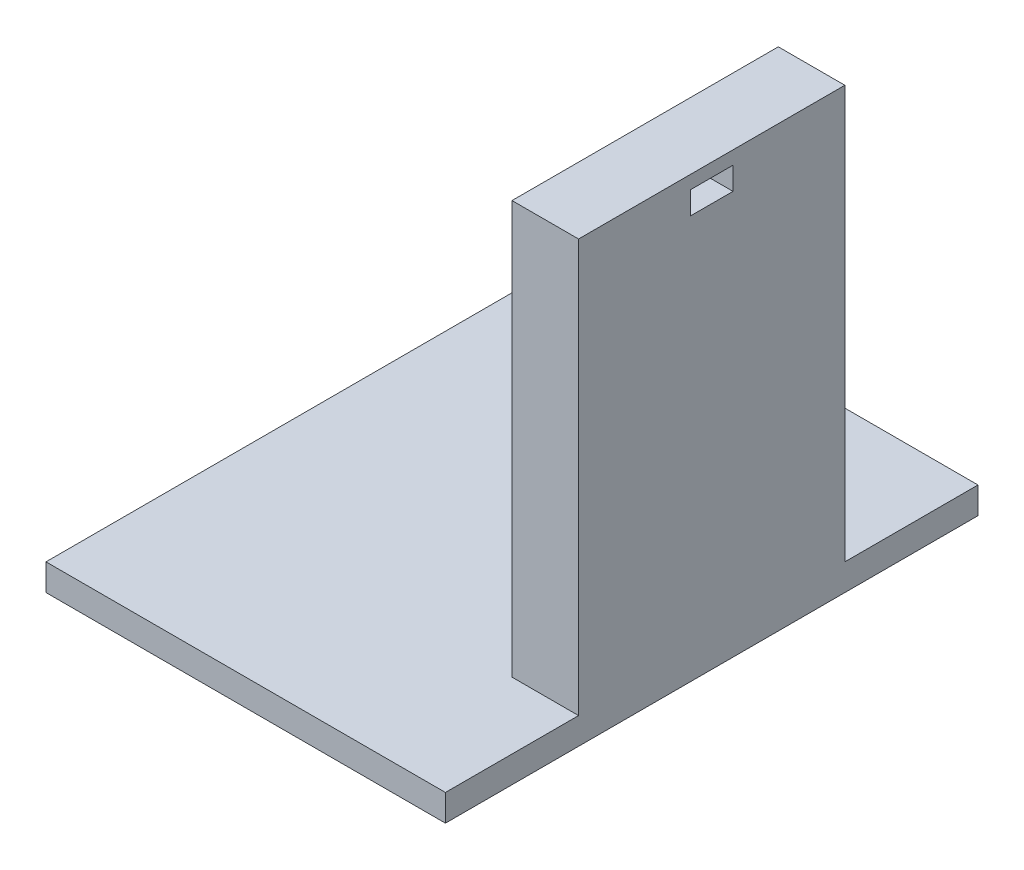
SolidWorks part; units mm, degrees
ref_plane "Plan de face" through (0, 0, 0) normal (0, 0, 1) x (1, 0, 0)
ref_plane "Plan de dessus" through (0, 0, 0) normal (0, 1, 0) x (1, 0, 0)
ref_plane "Plan de droite" through (0, 0, 0) normal (1, 0, 0) x (0, 0, -1)
sketch "Esquisse2" plane through (0, 0, 0) normal (0, 1, 0) x (1, 0, 0)
  line L0 (54.6919, 181.7) -> (54.6919, -18.3)
  line L1 (-95.3081, 181.7) -> (54.6919, 181.7)
  line L2 (-95.3081, 181.7) -> (-95.3081, -18.3)
  line L3 (-95.3081, -18.3) -> (54.6919, -18.3)
extrude "Boss.-Extru.6" add sketch "Esquisse2" along normal blind 10
sketch "Esquisse4" plane through (0, 0, 0) normal (0, 1, 0) x (1, 0, 0)
  line L0 (29.6919, 31.7) -> (54.6919, 31.7)
  line L1 (29.6919, 31.7) -> (29.6919, 131.7)
  line L2 (29.6919, 131.7) -> (54.6919, 131.7)
  line L3 (54.6919, 31.7) -> (54.6919, 131.7)
  line L4 (54.6919, -18.3) -> (54.6919, 181.7) construction
  line L5 (54.6919, -18.3) -> (54.6919, 181.7)
extrude "Boss.-Extru.7" add sketch "Esquisse4" along normal blind 160 contours L0 L3 L2 L1
sketch "Esquisse8" plane through (29.6919, 0, 0) normal (-1, 0, 0) x (0, 0, 1)
  line L0 (-93.9, 139.9717) -> (-69.5, 139.9717)
  line L1 (-93.9, 139.9717) -> (-93.9, 160)
  line L2 (-93.9, 160) -> (-69.5, 160)
  line L3 (-69.5, 139.9717) -> (-69.5, 160)
  line L4 (-31.7, 160) -> (-131.7, 160) construction
  point P6 (-81.7, 160)
  dimension "D1" = 20.0283
  dimension "D2" = 24.4
extrude "Enlèv. mat.-Extru.1" cut sketch "Esquisse8" against normal blind 12.2
sketch "Esquisse9" plane through (41.8919, 0, 0) normal (-1, 0, 0) x (0, 0, 1)
  line L0 (-87.7, 158.4859) -> (-87.7, 153.4859) construction
  line L1 (-87.7, 153.4859) -> (-75.7, 153.4859) construction
  line L2 (-75.7, 153.4859) -> (-75.7, 158.4859) construction
  line L3 (-75.7, 158.4859) -> (-87.7, 158.4859) construction
  line L4 (-81.7, 160) -> (-81.7, 158.4859) construction
  line L6 (-69.5, 160) -> (-93.9, 160) construction
  line L7 (-87.7, 158.4859) -> (-87.7, 153.4859)
  line L8 (-87.7, 153.4859) -> (-75.7, 153.4859)
  line L9 (-75.7, 153.4859) -> (-75.7, 158.4859)
  line L10 (-75.7, 158.4859) -> (-87.7, 158.4859)
  point P6 (-81.7, 158.4859)
  dimension "D1" = 1.5141
  dimension "D2" = 5
  dimension "D3" = 12
extrude "Enlèv. mat.-Extru.2" cut sketch "Esquisse9" against normal blind 42.2
sketch "Esquisse11" plane through (41.8919, 0, 0) normal (-1, 0, 0) x (0, 0, 1)
  line L0 (-69.5, 160) -> (-93.9, 160) construction
  line L1 (-89.7, 160) -> (-73.7, 160)
  line L2 (-89.7, 160) -> (-89.7, 151.4859)
  line L3 (-89.7, 151.4859) -> (-73.7, 151.4859)
  line L4 (-73.7, 160) -> (-73.7, 151.4859)
  line L5 (-87.7, 155.7429) -> (-89.7, 155.7429) construction
  line L6 (-87.7, 158.4859) -> (-87.7, 153.4859) construction
  line L7 (-75.7, 155.9859) -> (-73.7, 155.9859) construction
  line L8 (-75.7, 153.4859) -> (-75.7, 158.4859) construction
  line L9 (-81.7, 153.4859) -> (-81.7, 151.4859) construction
  line L10 (-87.7, 153.4859) -> (-75.7, 153.4859) construction
  dimension "D1" = 2
  dimension "D2" = 2
  dimension "D3" = 2
extrude "Enlèv. mat.-Extru.3" cut sketch "Esquisse11" against normal blind 42.2
sketch "Esquisse12" plane through (29.6919, 0, 0) normal (-1, 0, 0) x (0, 0, 1)
  line L0 (-94.4, 160) -> (-94.4, 139.97)
  line L1 (-93.9, 160) -> (-131.7, 160) construction
  line L3 (-69, 139.97) -> (-69, 160)
  line L4 (-31.7, 160) -> (-69.5, 160) construction
  line L5 (-69, 160) -> (-69.5, 160)
  line L6 (-69.5, 160) -> (-69.5, 139.9717)
  line L8 (-93.9, 139.9717) -> (-93.9, 160)
  line L9 (-93.9, 160) -> (-94.4, 160)
  line L10 (-79.5159, 139.9717) -> (-79.5159, 139.4717) construction
  line L11 (-69, 139.97) -> (-69.5, 139.9717)
  line L13 (-93.9, 139.9717) -> (-94.4, 139.97)
  dimension "D1" = 0.5
  dimension "D2" = 0.5
  dimension "D3" = 20.0283
  dimension "D4" = 20.03
  dimension "D5" = 20.03
extrude "Enlèv. mat.-Extru.6" cut sketch "Esquisse12" against normal blind 12.2
sketch "Esquisse13" plane through (0, 160, 0) normal (0, 1, 0) x (1, 0, 0)
  line L1 (29.6919, 131.7) -> (54.6919, 131.7)
  line L2 (29.6919, 131.7) -> (29.6919, 31.7)
  line L3 (29.6919, 31.7) -> (54.6919, 31.7)
  line L4 (54.6919, 131.7) -> (54.6919, 31.7)
extrude "Boss.-Extru.8" add sketch "Esquisse13" along normal blind 5
sketch "Esquisse14" plane through (29.6919, 0, 0) normal (-1, 0, 0) x (0, 0, 1)
  line L0 (-94.4, 160) -> (-94.4, 160.5)
  line L2 (-94.4, 160) -> (-69, 160)
  line L4 (-69, 160) -> (-69, 160.5)
  line L5 (-69, 160.5) -> (-94.4, 160.5)
  dimension "D1" = 0.5
extrude "Enlèv. mat.-Extru.7" cut sketch "Esquisse14" against normal blind 12.2
sketch "Esquisse19" plane through (41.8919, 0, 0) normal (-1, 0, 0) x (0, 0, 1)
  line L1 (-106.7, 5) -> (-56.7, 5)
  line L2 (-106.7, 5) -> (-106.7, 0)
  line L3 (-106.7, 0) -> (-56.7, 0)
  line L4 (-56.7, 5) -> (-56.7, 0)
  line L5 (-181.7, 0) -> (18.3, 0) construction
  point P8 (-81.7, 0)
  point P9 (-81.7, 0)
  dimension "D1" = 50
  dimension "D2" = 5
extrude "Enlèv. mat.-Extru.8" cut sketch "Esquisse19" along normal blind 150
sketch "Esquisse21" plane through (0, 0, 0) normal (1, 0, 0) x (0, 0, -1)
  line L0 (56.7, 5) -> (106.7, 5)
  line L1 (56.7, 5) -> (56.7, 0)
  line L2 (56.7, 0) -> (106.7, 0)
  line L3 (106.7, 5) -> (106.7, 0)
  line L4 (181.7, 0) -> (-18.3, 0) construction
  point P4 (81.7, 0)
  point P9 (81.7, 0)
  dimension "D1" = 5
  dimension "D2" = 50
extrude "Boss.-Extru.9" add sketch "Esquisse21" along normal blind 42 and the other way blind 75
sketch "Esquisse22" plane through (0, 0, 0) normal (0, 1, 0) x (1, 0, 0)
  line L0 (-85.1541, 56.7) -> (-85.1541, 106.7) construction
  line L1 (-75, 56.7) -> (-95.3081, 56.7) construction
  line L2 (-95.3081, 106.7) -> (-75, 106.7) construction
  circle A0 centre (-85.1541, 81.7) radius 5
  point P8 (-85.1541, 81.7)
  dimension "D1" = 10
extrude "Boss.-Extru.10" add sketch "Esquisse22" along normal blind 6
